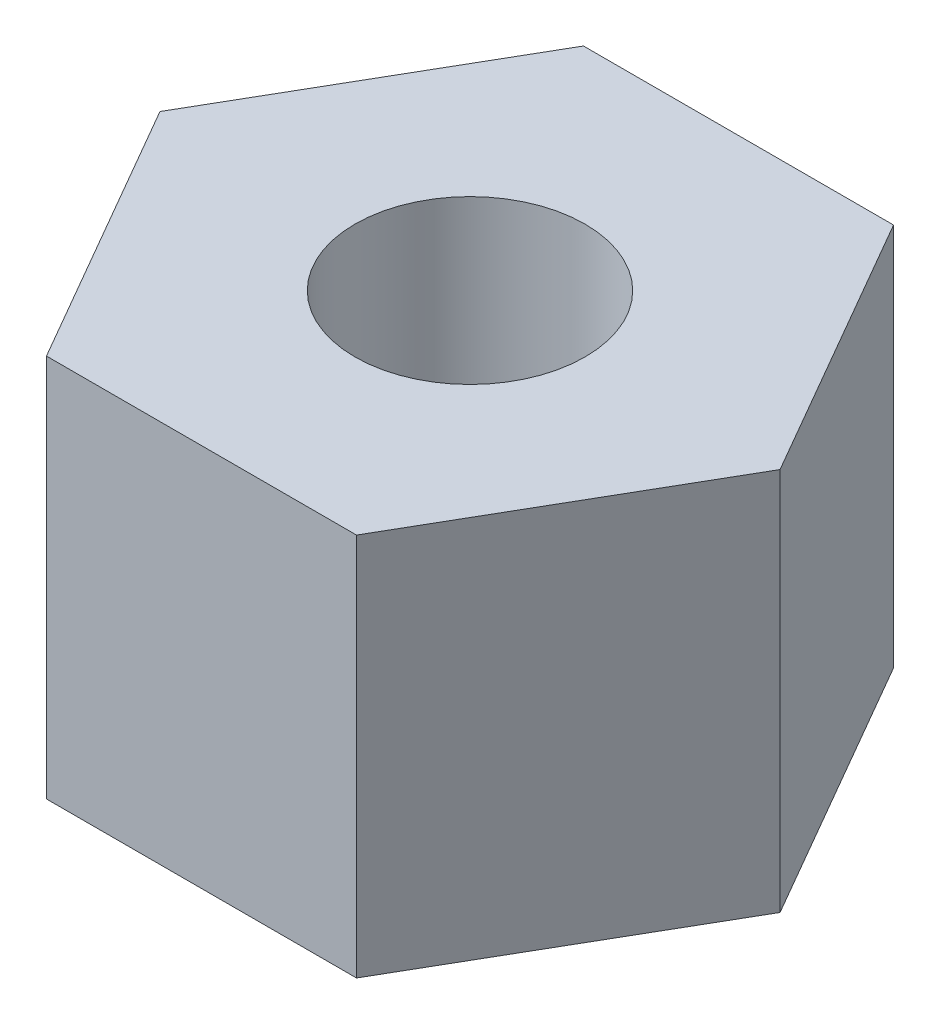
SolidWorks part; units mm, degrees
ref_plane "Alzado" through (0, 0, 0) normal (0, 0, 1) x (1, 0, 0)
ref_plane "Planta" through (0, 0, 0) normal (0, 1, 0) x (1, 0, 0)
ref_plane "Vista lateral" through (0, 0, 0) normal (1, 0, 0) x (0, 0, -1)
sketch "Croquis1" plane through (0, 0, 0) normal (0, 1, 0) x (1, 0, 0)
  line L1 (4.0415, 0) -> (2.0207, 3.5)
  line L2 (2.0207, 3.5) -> (-2.0207, 3.5)
  line L3 (-2.0207, 3.5) -> (-4.0415, 0)
  line L4 (-4.0415, 0) -> (-2.0207, -3.5)
  line L5 (-2.0207, -3.5) -> (2.0207, -3.5)
  line L6 (2.0207, -3.5) -> (4.0415, 0)
  circle A0 centre (0, 0) radius 1.5
  circle A1 centre (0, 0) radius 3.5 construction
  dimension "D1" = 3
  dimension "D2" = 7
extrude "Saliente-Extruir1" add sketch "Croquis1" along normal mid plane 5 contours L5 L6 L1 L2 L3 L4 A0
